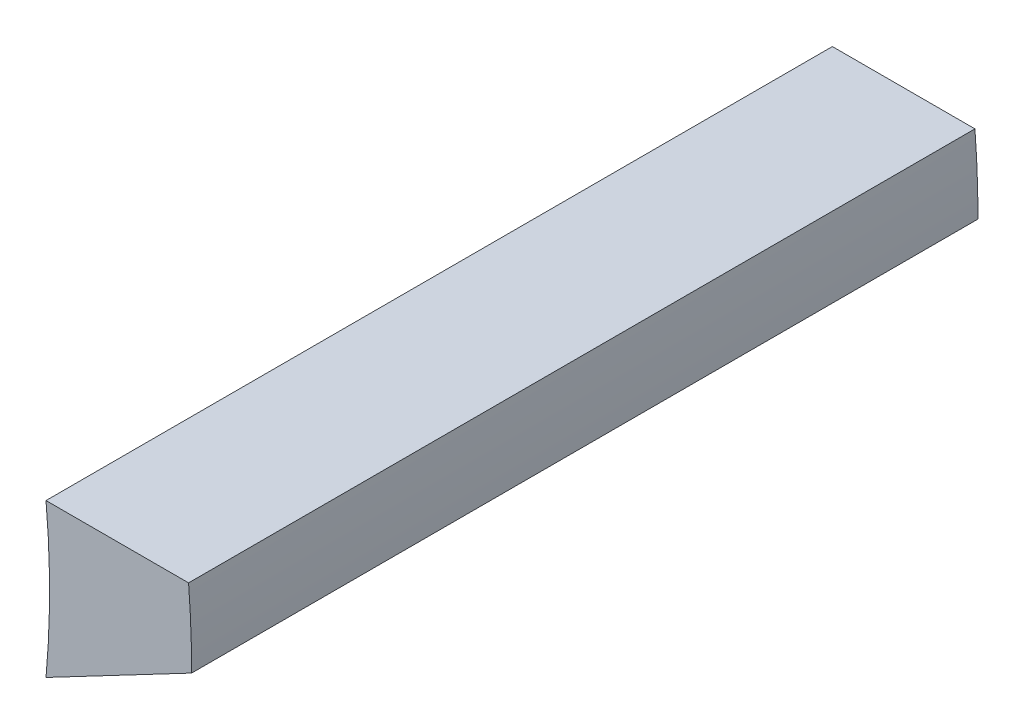
SolidWorks part; units mm, degrees
ref_plane "前视基准面" through (0, 0, 0) normal (0, 0, 1) x (1, 0, 0)
ref_plane "上视基准面" through (0, 0, 0) normal (0, 1, 0) x (1, 0, 0)
ref_plane "右视基准面" through (0, 0, 0) normal (1, 0, 0) x (0, 0, -1)
other "Configuration Table"
sketch "草图1" plane through (0, 0, 0) normal (0, 0, 1) x (1, 0, 0)
  line L0 (18.7119, 1.7536) -> (21.9756, 1.7536)
  line L1 (22.0455, 0) -> (18.7119, -1.7536)
  arc A0 (18.7119, -1.7536) -> (18.7119, 1.7536) centre (0, 0) ccw
  arc A1 (21.9756, 1.7536) -> (22.0455, 0) centre (0, 0) cw
extrude "凸台-拉伸1" add sketch "草图1" along normal blind 18
